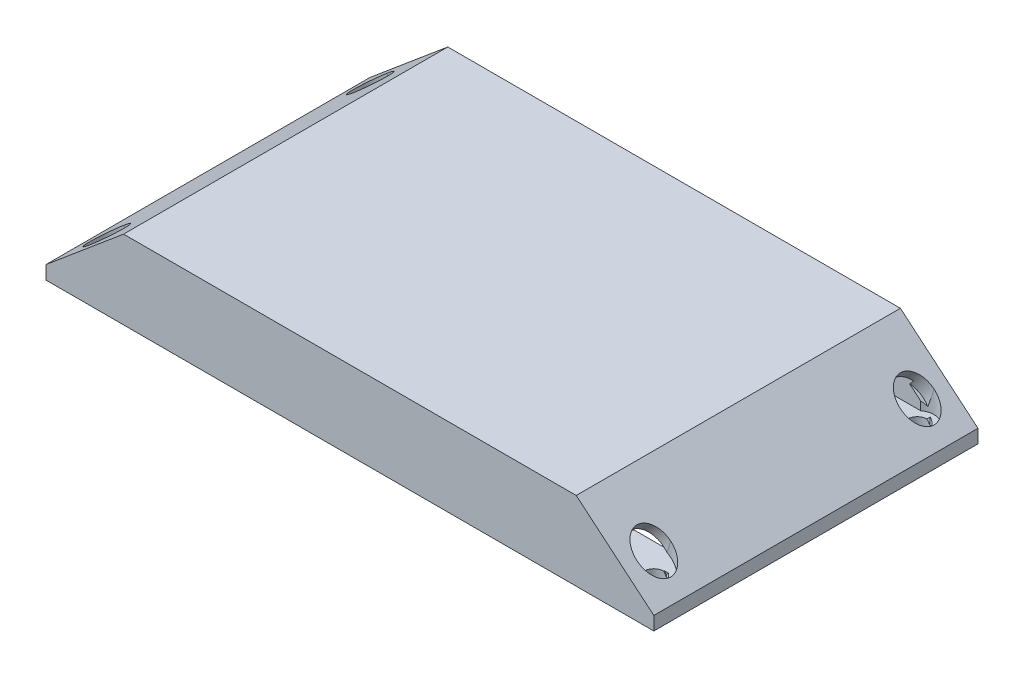
SolidWorks part; units mm, degrees
ref_plane "Přední rovina" through (0, 0, 0) normal (0, 0, 1) x (1, 0, 0)
ref_plane "Horní rovina" through (0, 0, 0) normal (0, 1, 0) x (1, 0, 0)
ref_plane "Pravá rovina" through (0, 0, 0) normal (1, 0, 0) x (0, 0, -1)
sketch "Skica1" plane through (0, 0, 0) normal (0, 1, 0) x (1, 0, 0)
  line L1 (0, 0) -> (90, 0)
  line L2 (0, 0) -> (0, 48)
  line L3 (0, 48) -> (90, 48)
  line L4 (90, 0) -> (90, 48)
  line L5 (2.5, 2.5) -> (87.5, 2.5)
  line L6 (2.5, 2.5) -> (2.5, 45.5)
  line L7 (2.5, 45.5) -> (87.5, 45.5)
  line L8 (87.5, 2.5) -> (87.5, 45.5)
  dimension "D1" = 48
  dimension "D2" = 90
  dimension "D3" = 2.5
  dimension "D4" = 2.5
  dimension "D5" = 2.5
  dimension "D6" = 2.5
extrude "Přidat vysunutím1" add sketch "Skica1" along normal blind 2
sketch "Skica2" plane through (0, 0, 0) normal (0, 0, 1) x (1, 0, 0)
  line L0 (0, 2) -> (11.4907, 11.6418)
  line L1 (0, 2) -> (90, 2) construction
  line L2 (90, 2) -> (78.5093, 11.6418)
  line L3 (11.4907, 11.6418) -> (78.5093, 11.6418)
  line L4 (0, 2) -> (90, 2)
  dimension "D1" = 15
  dimension "D2" = 40
  dimension "D3" = 15
  dimension "D4" = 40
extrude "Přidat vysunutím2" add sketch "Skica2" against normal blind 2.5
sketch "Skica3" plane through (0, 0, -2.5) normal (0, 0, -1) x (-1, 0, 0)
  line L0 (-90, 2) -> (-78.5093, 11.6418)
  line L1 (-78.5093, 11.6418) -> (-11.4907, 11.6418)
  line L2 (-11.4907, 11.6418) -> (0, 2)
  line L3 (0, 2) -> (-2.5, 2)
  line L4 (-2.5, 2) -> (-11.6072, 9.6418)
  line L5 (-11.6072, 9.6418) -> (-78.3928, 9.6418)
  line L6 (-78.3928, 9.6418) -> (-87.5, 2)
  line L7 (-90, 2) -> (0, 2) construction
  line L8 (-87.5, 2) -> (-90, 2) construction
  line L9 (-87.5, 2) -> (-90, 2)
  dimension "D1" = 2
extrude "Přidat vysunutím3" add sketch "Skica3" along normal blind 43 contours L0 L1 L2 L3 L4 L5 L6 L9
sketch "Skica4" plane through (0, 0, 0) normal (0, 0, 1) x (1, 0, 0)
  line L0 (0, 2) -> (11.4907, 11.6418)
  line L2 (90, 2) -> (78.5093, 11.6418)
  line L3 (11.4907, 11.6418) -> (78.5093, 11.6418)
  line L4 (0, 2) -> (90, 2)
  dimension "D1" = 15
  dimension "D3" = 15
extrude "Přidat vysunutím4" add sketch "Skica4" against normal blind 2.5 from offset 45.5 offset against normal yes
sketch "Skica5" plane through (0, 0, 0) normal (0, -1, 0) x (1, 0, 0)
  circle A0 centre (4.5, -4.5) radius 1.4
  circle A1 centre (4.5, -4.5) radius 2.5
  circle A2 centre (4.5, -43.5) radius 1.4
  circle A3 centre (4.5, -43.5) radius 2.5
  circle A4 centre (85.5, -4.5) radius 1.4
  circle A5 centre (85.5, -4.5) radius 2.5
  circle A6 centre (85.5, -43.5) radius 1.4
  circle A7 centre (85.5, -43.5) radius 2.5
  dimension "D3" = 2.8
  dimension "D4" = 5
  dimension "D6" = 2.8
  dimension "D7" = 5
  dimension "D9" = 2.8
  dimension "D10" = 5
  dimension "D12" = 2.8
  dimension "D13" = 5
extrude "Přidat vysunutím5" add sketch "Skica5" against normal blind 6
sketch "Skica6" plane through (0, 6, 0) normal (0, 1, 0) x (1, 0, 0)
  circle A0 centre (4.5, 43.5) radius 2.5
  circle A1 centre (4.5, 4.5) radius 2.5
  circle A2 centre (85.5, 4.5) radius 2.5
  circle A3 centre (85.5, 43.5) radius 2.5
  dimension "D1" = 5
  dimension "D2" = 5
  dimension "D3" = 5
  dimension "D4" = 5
extrude "Odebrat vysunutím1" cut sketch "Skica6" against normal blind 3.5
sketch "Skica7" plane through (-0.9848, 1.1736, 0) normal (-0.6428, 0.766, 0) x (0.766, 0.6428, 0)
  ellipse E0 centre (7.1599, 4.5) end of major axis (10.4217, 4.5813) minor radius 2.4992
  ellipse E1 centre (7.1599, 4.5) end of major axis (10.4234, 4.5) minor radius 2.5 (7.5085, 6.9857) -> (7.5085, 2.0143) ccw construction
  ellipse E2 centre (7.1599, 43.5) end of major axis (10.4234, 43.5) minor radius 2.5
  ellipse E3 centre (7.1599, 43.5) end of major axis (10.4234, 43.5) minor radius 2.5 (7.5085, 45.9857) -> (7.5085, 41.0143) ccw construction
extrude "Odebrat vysunutím2" cut sketch "Skica7" against normal blind 2.5
sketch "Skica8" plane through (38.1706, 45.49, 0) normal (0.6428, 0.766, 0) x (0.766, -0.6428, 0)
  ellipse E0 centre (61.7841, 43.5) end of major axis (65.0476, 43.5) minor radius 2.5
  ellipse E1 centre (61.7841, 43.5) end of major axis (65.0476, 43.5) minor radius 2.5 (61.4355, 41.0143) -> (61.4355, 45.9857) ccw construction
  ellipse E2 centre (61.7841, 4.5) end of major axis (65.0476, 4.5) minor radius 2.5
  ellipse E3 centre (61.7841, 4.5) end of major axis (65.0476, 4.5) minor radius 2.5 (61.4355, 2.0143) -> (61.4355, 6.9857) ccw construction
extrude "Odebrat vysunutím3" cut sketch "Skica8" against normal blind 2.5
sketch "Skica10" plane through (0, 0, 0) normal (0, -1, 0) x (1, 0, 0)
  line L0 (2.5, -42) -> (6.5, -42)
  line L1 (6.5, -42) -> (6, -45.5)
  line L2 (6, -45.5) -> (13.5, -45.5)
  line L3 (84, -45.5) -> (6, -45.5) construction
  line L4 (13.5, -45.5) -> (13.5, -39)
  line L5 (13.5, -39) -> (2.5, -39)
  line L6 (2.5, -42) -> (2.5, -6) construction
  line L7 (2.5, -39) -> (2.5, -42)
  line L8 (2.5, -6) -> (6.5192, -6)
  line L9 (6.5192, -6) -> (6, -2.5)
  line L10 (6, -2.5) -> (13.5, -2.5)
  line L11 (11.6072, -2.5) -> (78.3928, -2.5) construction
  line L12 (13.5, -2.5) -> (13.5, -9)
  line L13 (13.5, -9) -> (2.5, -9)
  line L14 (2.5, -42) -> (2.5, -6) construction
  line L15 (2.5, -9) -> (2.5, -6)
  line L16 (87.5, -6) -> (83.5, -6)
  line L17 (83.5, -6) -> (84, -2.5)
  line L18 (84, -2.5) -> (76.5, -2.5)
  line L19 (6, -2.5) -> (84, -2.5) construction
  line L20 (76.5, -2.5) -> (76.5, -9)
  line L21 (76.5, -9) -> (87.5, -9)
  line L22 (87.5, -6) -> (87.5, -42) construction
  line L23 (87.5, -9) -> (87.5, -6)
  line L24 (87.5, -42) -> (83.5, -42)
  line L25 (83.5, -42) -> (84, -45.5)
  line L26 (84, -45.5) -> (76.5, -45.5)
  line L27 (76.5, -45.5) -> (76.5, -39)
  line L28 (76.5, -39) -> (87.5, -39)
  line L29 (87.5, -39) -> (87.5, -42)
  arc A0 (4.5, -46) -> (4.5, -41) centre (4.5, -43.5) ccw construction
  arc A1 (84, -2.5) -> (87.5, -6) centre (85.5, -4.5) ccw construction
  arc A2 (87.5, -42) -> (84, -45.5) centre (85.5, -43.5) ccw construction
  ellipse E0 centre (4.5, -4.5) end of major axis (2.7377, -2.704) minor radius 2.4826 (4.5339, -6.9998) -> (4.767, -2.0184) ccw construction
  dimension "D1" = 6.5
  dimension "D2" = 7.5
  dimension "D3" = 6.5
  dimension "D4" = 7.5
  dimension "D5" = 6.5
  dimension "D6" = 7.5
  dimension "D7" = 6.5
extrude "Přidat vysunutím7" add sketch "Skica10" against normal blind 2.5
sketch "Skica12" plane through (0, 0, 0) normal (0, -1, 0) x (1, 0, 0)
  line L0 (76.5, -9) -> (76.5, -2.5)
  line L1 (76.5, -2.5) -> (78, -2.5)
  line L2 (11.6072, -2.5) -> (78.3928, -2.5) construction
  line L3 (78, -2.5) -> (78, -9)
  line L4 (76.5, -9) -> (87.5, -9) construction
  line L5 (78, -9) -> (76.5, -9)
  line L6 (76.5, -45.5) -> (78, -45.5)
  line L7 (78, -45.5) -> (78, -39)
  line L8 (87.5, -39) -> (76.5, -39) construction
  line L9 (78, -39) -> (76.5, -39)
  line L10 (76.5, -39) -> (76.5, -45.5)
  line L11 (13.5, -45.5) -> (12, -45.5)
  line L12 (11.6072, -45.5) -> (78.3928, -45.5) construction
  line L13 (12, -45.5) -> (12, -39)
  line L14 (12, -39) -> (13.5, -39)
  line L15 (13.5, -45.5) -> (13.5, -39) construction
  line L16 (13.5, -39) -> (13.5, -45.5)
  line L17 (13.5, -2.5) -> (13.5, -9)
  line L18 (13.5, -9) -> (12, -9)
  line L19 (2.5, -9) -> (13.5, -9) construction
  line L20 (12, -9) -> (12, -2.5)
  line L21 (12, -2.5) -> (13.5, -2.5)
  dimension "D1" = 1.5
  dimension "D2" = 1.5
extrude "Přidat vysunutím8" add sketch "Skica12" against normal blind 11.5
